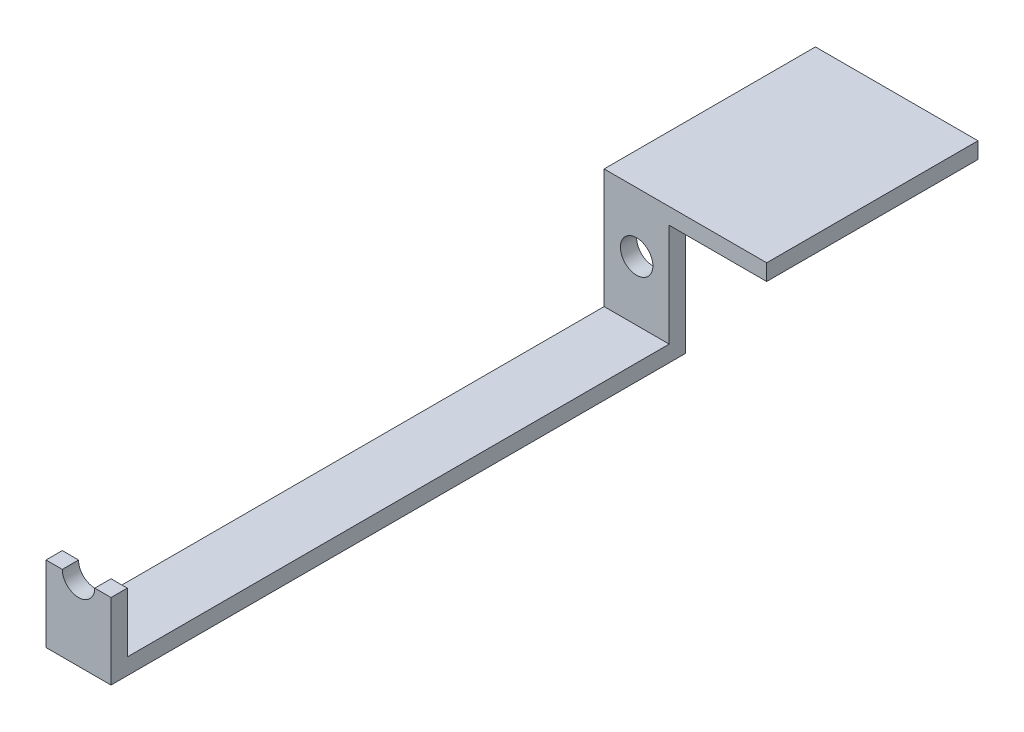
SolidWorks part; units mm, degrees
ref_plane "前视基准面" through (0, 0, 0) normal (0, 0, 1) x (1, 0, 0)
ref_plane "上视基准面" through (0, 0, 0) normal (0, 1, 0) x (1, 0, 0)
ref_plane "右视基准面" through (0, 0, 0) normal (1, 0, 0) x (0, 0, -1)
sketch "草图2" plane through (0, 0, 0) normal (1, 0, 0) x (0, 0, -1)
  line L0 (0, 16.5) -> (0, -15.5769) construction
  line L1 (-53, 0) -> (53, 0)
  line L2 (53, 0) -> (53, 20)
  line L4 (50, 20) -> (50, 3)
  line L5 (50, 3) -> (-50, 3)
  line L6 (50, 20) -> (50, 25)
  line L7 (-50, 14) -> (-50, 3)
  line L8 (-53, 0) -> (-53, 14)
  line L9 (-53, 14) -> (-50, 14)
  line L10 (50, 25) -> (89, 25)
  line L11 (89, 25) -> (89, 22)
  line L12 (89, 22) -> (53, 22)
  line L13 (53, 22) -> (53, 20)
  point P10 (0, 3)
  point P13 (0, 0)
  dimension "D1" = 3
  dimension "D2" = 20
  dimension "D3" = 3
  dimension "D4" = 53
  dimension "D5" = 14
  dimension "D6" = 2
  dimension "D7" = 3
  dimension "D8" = 36
extrude "凸台-拉伸1" add sketch "草图2" along normal blind 12
sketch "草图3" plane through (0, 0, -53) normal (0, 0, -1) x (-1, 0, 0)
  line L0 (-6, 22) -> (-6, 0) construction
  line L2 (-12, 0) -> (0, 0) construction
  line L3 (-12, 22) -> (0, 22) construction
  circle A0 centre (-6, 14) radius 3
  dimension "D1" = 6
  dimension "D2" = 8
extrude "切除-拉伸1" cut sketch "草图3" against normal up to surface (106 mm away) up to face at (6, 7, 53)
sketch "草图5" plane through (12, 0, 0) normal (1, 0, 0) x (0, 0, -1)
  line L1 (89, 22) -> (50, 22)
  line L2 (89, 22) -> (89, 25)
  line L3 (89, 25) -> (50, 25)
  line L4 (50, 22) -> (50, 25)
extrude "凸台-拉伸2" add sketch "草图5" along normal blind 18
